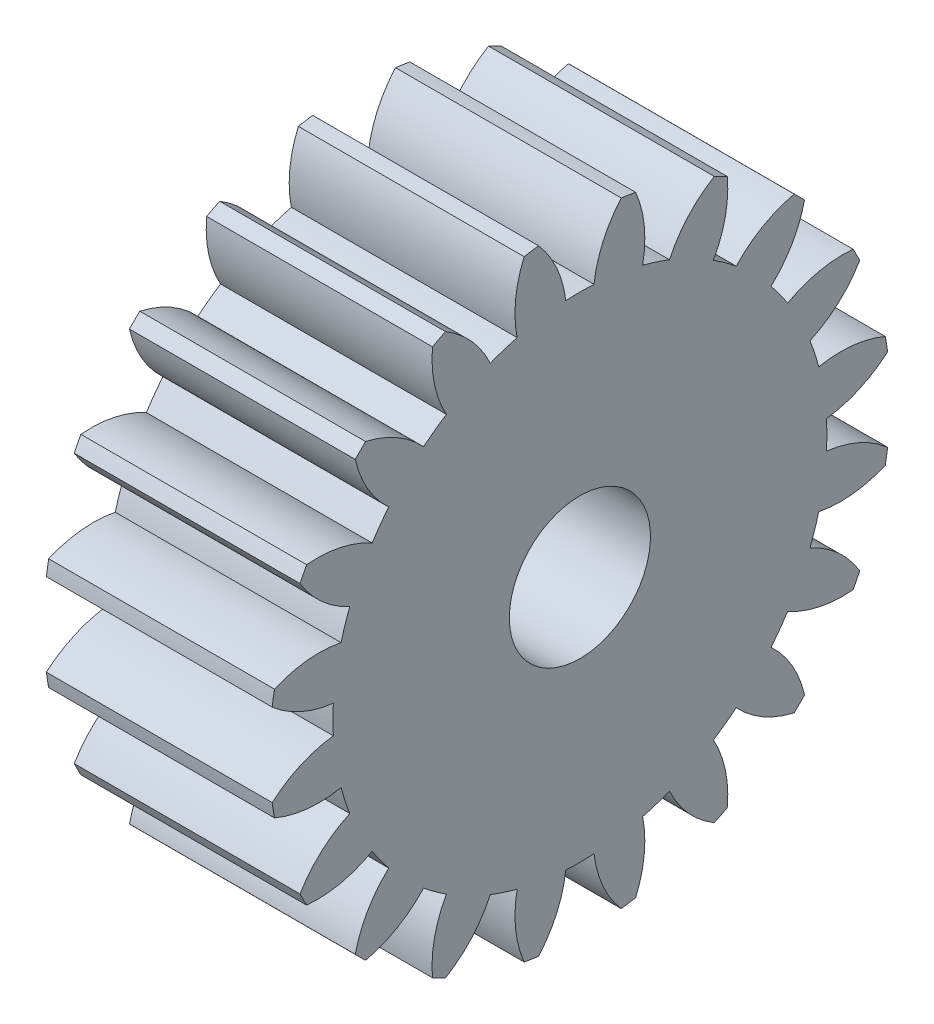
SolidWorks part; units mm, degrees
ref_plane "Plane1" through (0, 0, 0) normal (0, 0, 1) x (1, 0, 0)
ref_plane "Plane2" through (0, 0, 0) normal (0, 1, 0) x (1, 0, 0)
ref_plane "Plane3" through (0, 0, 0) normal (1, 0, 0) x (0, 0, -1)
other "Configuration Table"
sketch "HoldingSke" plane through (0, 0, 0) normal (0, 1, 0) x (1, 0, 0)
  line L0 (0, 0) -> (0.9397, -0.342)
  line L1 (-15, 0) -> (100, 0) construction
  line L2 (0, 0) -> (-2.1039, 2.3779)
  line L3 (0, 0) -> (-11.863, 4.5341)
  line L4 (0, 0) -> (8.1152, 2.9537)
  line L5 (0, 0) -> (-46.8476, -17.4728)
  line L6 (0, 0) -> (-6.6317, -4.4744)
  line L7 (-2.1039, 2.3779) -> (8.6586, 51.2059)
  line L8 (-76.2, 54.61) -> (-75.3, 54.61)
  line L9 (-71.009, 38.7566) -> (-53.1078, 45.2721)
  line L10 (-76.2, 71.12) -> (104.1128, 71.12)
  line L11 (0, 0) -> (-8, 0)
  line L12 (-76.2, 101.6) -> (-76.162, 101.6)
  line L13 (24.9733, 27.94) -> (52.9518, 28.4284)
  line L14 (24.9733, 27.94) -> (24.9743, 27.94)
  line L15 (24.9733, 27.94) -> (100.4006, 29.5858)
  line L16 (-63.627, -1) -> (-12.827, -1)
  circle A0 centre (0, 0) radius 2.5
  circle A1 centre (0, 0) radius 8.749
  circle A2 centre (0, 0) radius 37.5
  circle A3 centre (0, 0) radius 2.5
  dimension "MHD" = 17.498
  dimension "Hub_dia" = 75
  dimension "Bore" = 5
  dimension "MBD" = 5
  dimension "Num_teeth" = 20
  dimension "Pitch" = 1
  dimension "Overall_len" = 50
  dimension "Show_teeth" = 20
  dimension "Thickness" = 8
  dimension "OAL" = 50.0001
  dimension "T_dim" = 0.9
  dimension "Ap" = 20
  dimension "H" = 19.05
  dimension "Pitch_radius" = 180.3128
  dimension "Width" = 8
  dimension "Backlash" = 0.038
  dimension "Addendum_fac" = 1
  dimension "Dedendum_fac" = 1.25
  dimension "Clearance_fac" = 0.25
  dimension "Dedendum_add" = 0.001
  dimension "Module" = 1
sketch "BasProSke" plane through (0, 0, 0) normal (0, 1, 0) x (1, 0, 0)
  line L0 (-10, 0) -> (60, 0) construction
  line L1 (0, 0) -> (0, 11)
  line L2 (0, 0) -> (8, 0)
  line L3 (8, 0) -> (8, 11)
  line L4 (8, 11) -> (0, 11)
  dimension "Thickness" = 8
  dimension "Diameter" = 22
revolve "Base-Revolve" add sketch "BasProSke" angle 360 about L0
sketch "TooCutSke" plane through (0, 0, 0) normal (1, 0, 0) x (0, 0, -1)
  line L1 (0, 0) -> (0, 107) construction
  line L2 (0, 0) -> (-0.8511, 9.9637) construction
  line L3 (0, 0) -> (-3.1206, 19.7028) construction
  line L4 (-0.8511, 9.9637) -> (-1.5603, 9.8514) construction
  arc A0 (0.4999, 8.7347) -> (-0.4999, 8.7347) centre (0, 0) ccw
  arc A1 (1.4852, 10.9249) -> (-1.4852, 10.9249) centre (0, 0) ccw
  circle A2 centre (0, 0) radius 10 construction
  circle A3 centre (0, 0) radius 9.3969 construction
  arc A4 (-0.4999, 8.7347) -> (-1.4852, 10.9249) centre (-4.4722, 8.2645) ccw
  arc A5 (1.4852, 10.9249) -> (0.4999, 8.7347) centre (4.4722, 8.2645) ccw
  dimension "Root_dia" = 17.498
  dimension "Overcut_dia" = 22.0508
  dimension "Pitch_dia" = 20
  dimension "Base_dia" = 18.7939
  dimension "Flank_rad" = 4
  dimension "Half_ang" = 9
  dimension "Half_CT" = 0.7181
extrude "ToothCut" cut sketch "TooCutSke" along normal through all
fillet "Breaks" [suppressed] radius 0.02
fillet "RootFillets" [suppressed] radius 0.251
pattern_circular "TeethCuts" count 20 every 18 about axis through (-10, 0, 0) along (1, 0, 0) of "ToothCut", "RootFillets", "Breaks"
sketch "HubNeaOneSke" plane through (0, 0, 0) normal (-1, 0, 0) x (0, 0, 1)
  circle A0 centre (0, 0) radius 8.749
  dimension "Diameter" = 17.498
extrude "HubNearOne" [suppressed] add sketch "HubNeaOneSke" along normal blind 42.0001
sketch "HubNeaBotSke" plane through (0, 0, 0) normal (-1, 0, 0) x (0, 0, 1)
  circle A0 centre (0, 0) radius 8.749
  dimension "Diameter" = 17.498
extrude "HubNearBoth" [suppressed] add sketch "HubNeaBotSke" along normal blind 21
ref_plane "FarPln" through (8, 0, 0) normal (1, 0, 0) x (0, 0, -1)
sketch "HubFarSke" plane through (8, 0, 0) normal (1, 0, 0) x (0, 0, -1)
  circle A0 centre (0, 0) radius 8.749
  dimension "Diameter" = 17.498
extrude "HubFar" [suppressed] add sketch "HubFarSke" along normal blind 21
sketch "BorSke" plane through (0, 0, 0) normal (1, 0, 0) x (0, 0, -1)
  circle A0 centre (0, 0) radius 2.5
  dimension "Diameter" = 5
extrude "Bore" cut sketch "BorSke" along normal mid plane 100.0001
sketch "KeySke" plane through (0, 0, 0) normal (1, 0, 0) x (0, 0, -1)
  line L0 (-1, 0) -> (-1, 3.4)
  line L1 (-1, 3.4) -> (1, 3.4)
  line L2 (1, 3.4) -> (1, 0)
  line L3 (0, 0) -> (0, 34) construction
  line L4 (-1, 0) -> (1, 0)
  dimension "Offset" = 3.4
  dimension "Width" = 2
extrude "Keyway" [suppressed] cut sketch "KeySke" along normal mid plane 100.0001
pattern_circular "Keyway2" [suppressed] count 2 every 90 about axis through (-10, 0, 0) along (1, 0, 0)
equation "' \"Module@HoldingSke\" = 6.35"
equation "' \"Num_teeth@HoldingSke\" = 12"
equation "' \"Ap@HoldingSke\" =  20"
equation "' \"Ap@HoldingSke\" = 20"
equation "' \"Width@HoldingSke\" = 0.5 * 25.4"
equation "' \"Hub_dia@HoldingSke\"= 1 * 25.4"
equation "' \"Hub_dia@HoldingSke\" = 1 * 25.4"
equation "' \"Overall_len@HoldingSke\" = 1.0 * 25.4"
equation "' \"Bore@HoldingSke\" = 0.75 * 25.4"
equation "' \"T_dim@HoldingSke\" = 0.1 * 25.4"
equation "' \"Width@KeySke\" = 0.25 * 25.4"
equation "' \"Show_teeth@HoldingSke\" = 13"
equation "' \"Backlash@HoldingSke\" = 0.009 * 25.4"
equation "' \"Addendum_fac@HoldingSke\" = 1.0"
equation "' \"Dedendum_fac@HoldingSke\" = 1.25"
equation "' \"Dedendum_add@HoldingSke\" = 0.00005 * 25.4"
equation "' \"Clearance_fac@HoldingSke\" = 0.25"
equation "\"Pitch@HoldingSke\" = 1 / \"Module@HoldingSke\""
equation "\"Overcut_dia@TooCutSke\" = (\"Num_teeth@HoldingSke\" + 2 * \"Addendum_fac@HoldingSke\") / \"Pitch@HoldingSke\" + 0.002 * 25.4"
equation "\"Pitch_dia@TooCutSke\" = \"Num_teeth@HoldingSke\" / \"Pitch@HoldingSke\""
equation "\"Base_dia@TooCutSke\" = \"Num_teeth@HoldingSke\" / \"Pitch@HoldingSke\" * cos((\"Ap@HoldingSke\"  * 3.14159265 / 180))"
equation "\"Root_dia@TooCutSke\" = (\"Num_teeth@HoldingSke\" + 2) / \"Pitch@HoldingSke\" - 2 * (\"Addendum_fac@HoldingSke\" + \"Dedendum_fac@HoldingSke\") / \"Pitch@HoldingSke\" - \"Dedendum_add@HoldingSke\" * 2"
equation "\"Half_ang@TooCutSke\" = 180 / \"Num_teeth@HoldingSke\""
equation "\"Half_CT@TooCutSke\" = \"Num_teeth@HoldingSke\" / \"Pitch@HoldingSke\" * sin((3.14159265 / 2 / \"Num_teeth@HoldingSke\")) / 2 - 7 * \"Backlash@HoldingSke\" / 4"
equation "\"Flank_rad@TooCutSke\" = \"Num_teeth@HoldingSke\" / \"Pitch@HoldingSke\" / 5"
equation "\"Radius@RootFillets\" = \"Clearance_fac@HoldingSke\" / \"Pitch@HoldingSke\" + \"Dedendum_add@HoldingSke\""
equation "\"Break_rad@Breaks\" = 0.02 / \"Pitch@HoldingSke\""
equation "\"Thickness@HoldingSke\" = \"Width@HoldingSke\""
equation "\"OAL@HoldingSke\" = \"Thickness@HoldingSke\""
equation "\"MHD@HoldingSke\" = (\"Num_teeth@HoldingSke\" + 2) / \"Pitch@HoldingSke\" - 2 * (\"Addendum_fac@HoldingSke\" + \"Dedendum_fac@HoldingSke\")  / \"Pitch@HoldingSke\" - \"Dedendum_add@HoldingSke\" * 2"
equation "\"MBD@HoldingSke\" = (\"Num_teeth@HoldingSke\" + 2) / \"Pitch@HoldingSke\" - 2 * (\"Addendum_fac@HoldingSke\" + \"Dedendum_fac@HoldingSke\")  / \"Pitch@HoldingSke\" - \"Dedendum_add@HoldingSke\" * 2 - 0.002 * 25.4"
equation "\"MHD@HoldingSke\" = ((sgn( \"MHD@HoldingSke\" - \"Hub_dia@HoldingSke\" )-1)*( \"MHD@HoldingSke\" - \"Hub_dia@HoldingSke\" ))/-2+ \"Hub_dia@HoldingSke\""
equation "\"MBD@HoldingSke\" = ((sgn( \"MBD@HoldingSke\" - \"Bore@HoldingSke\" )-1)*( \"MBD@HoldingSke\" - \"Bore@HoldingSke\" ))/-2+ \"Bore@HoldingSke\""
equation "\"OAL@HoldingSke\" = ((sgn( \"OAL@HoldingSke\" - \"Overall_len@HoldingSke\" )+1)*( \"OAL@HoldingSke\" - \"Overall_len@HoldingSke\" ))/2 + \"Overall_len@HoldingSke\" + 0.000002 * 25.4"
equation "\"Num_teeth@TeethCuts\" = int( \"Show_teeth@HoldingSke\" ) + 1"
equation "\"Num_teeth@TeethCuts\" = ((sgn( \"Num_teeth@TeethCuts\" - \"Num_teeth@HoldingSke\" )-1)*( \"Num_teeth@TeethCuts\" - \"Num_teeth@HoldingSke\" ))/-2+ \"Num_teeth@HoldingSke\""
equation "\"Num_teeth@TeethCuts\" = ((sgn( \"Num_teeth@TeethCuts\" - 2.0)+1)*( \"Num_teeth@TeethCuts\" - 2.0))/2 +2.0"
equation "\"Angle@TeethCuts\" = 360.0 / \"Num_teeth@HoldingSke\""
equation "\"Diameter@BasProSke\" = (\"Num_teeth@HoldingSke\" + 2 * \"Addendum_fac@HoldingSke\") / \"Pitch@HoldingSke\""
equation "\"Thickness@BasProSke\"  = \"Thickness@HoldingSke\""
equation "' \"Fillet_rad@BasProSke\" =  \"Thickness@HoldingSke\" * 0.05"
equation "' \"Fillet_rad@BasProSke\" = \"Thickness@HoldingSke\" * 0.05"
equation "\"MHD@HoldingSke\" = ((sgn( \"MHD@HoldingSke\" - \"Root_dia@TooCutSke\" )-1)*( \"MHD@HoldingSke\" - \"Root_dia@TooCutSke\" ))/-2+ \"Root_dia@TooCutSke\""
equation "\"Diameter@HubNeaOneSke\" = \"MHD@HoldingSke\""
equation "\"Length@HubNearOne\" = \"OAL@HoldingSke\" - \"Thickness@BasProSke\""
equation "\"Diameter@HubNeaBotSke\" = \"MHD@HoldingSke\""
equation "\"Length@HubNearBoth\" = ( \"OAL@HoldingSke\" - \"Thickness@BasProSke\" ) / 2.0"
equation "\"Thickness@FarPln\" = \"Thickness@BasProSke\""
equation "\"Diameter@HubFarSke\" = \"MHD@HoldingSke\""
equation "\"Length@HubFar\" = ( \"OAL@HoldingSke\" - \"Thickness@BasProSke\" ) / 2.0"
equation "\"Diameter@BorSke\" = \"MBD@HoldingSke\""
equation "\"D1@Bore\" = \"OAL@HoldingSke\" * 2.0"
equation "\"D1@Keyway\" = \"OAL@HoldingSke\" * 2.0"
equation "\"Offset@KeySke\" = \"T_dim@HoldingSke\" + \"MBD@HoldingSke\" / 2.0"
